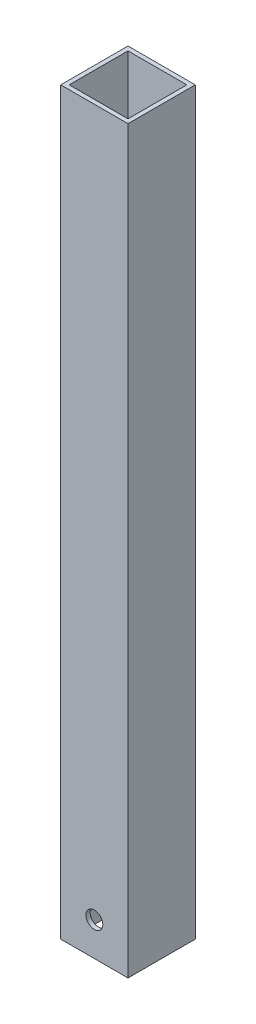
SolidWorks part; units mm, degrees
ref_plane "Front Plane" through (0, 0, 0) normal (0, 0, 1) x (1, 0, 0)
ref_plane "Top Plane" through (0, 0, 0) normal (0, 1, 0) x (1, 0, 0)
ref_plane "Right Plane" through (0, 0, 0) normal (1, 0, 0) x (0, 0, -1)
sketch "Sketch1" plane through (0, 0, 0) normal (0, 1, 0) x (1, 0, 0)
  line L1 (-12.7, -12.7) -> (12.7, -12.7)
  line L2 (-12.7, -12.7) -> (-12.7, 12.7)
  line L3 (-12.7, 12.7) -> (12.7, 12.7)
  line L4 (12.7, -12.7) -> (12.7, 12.7)
  line L5 (-12.7, -12.7) -> (12.7, 12.7) construction
  line L6 (-12.7, 12.7) -> (12.7, -12.7) construction
  line L7 (-11.1125, -11.1125) -> (11.1125, -11.1125)
  line L8 (-11.1125, -11.1125) -> (-11.1125, 11.1125)
  line L9 (-11.1125, 11.1125) -> (11.1125, 11.1125)
  line L10 (11.1125, -11.1125) -> (11.1125, 11.1125)
  line L11 (-11.1125, -11.1125) -> (11.1125, 11.1125) construction
  line L12 (-11.1125, 11.1125) -> (11.1125, -11.1125) construction
  point P0 (0, 0)
  point P6 (0, 0)
  dimension "D1" = 25.4
  dimension "D2" = 25.4
  dimension "D3" = 1.5875
  dimension "D4" = 1.5875
extrude "Boss-Extrude1" add sketch "Sketch1" along normal blind 279.4
sketch "Sketch2" plane through (0, 0, 12.7) normal (0, 0, 1) x (1, 0, 0)
  line L0 (12.7, 279.4) -> (12.7, 0) construction
  line L1 (-12.7, 0) -> (12.7, 0) construction
  circle A0 centre (0, 12.7) radius 3.175
  dimension "D1" = 6.35
  dimension "D2" = 12.7
  dimension "D3" = 12.7
extrude "Cut-Extrude1" cut sketch "Sketch2" against normal blind 25.4
